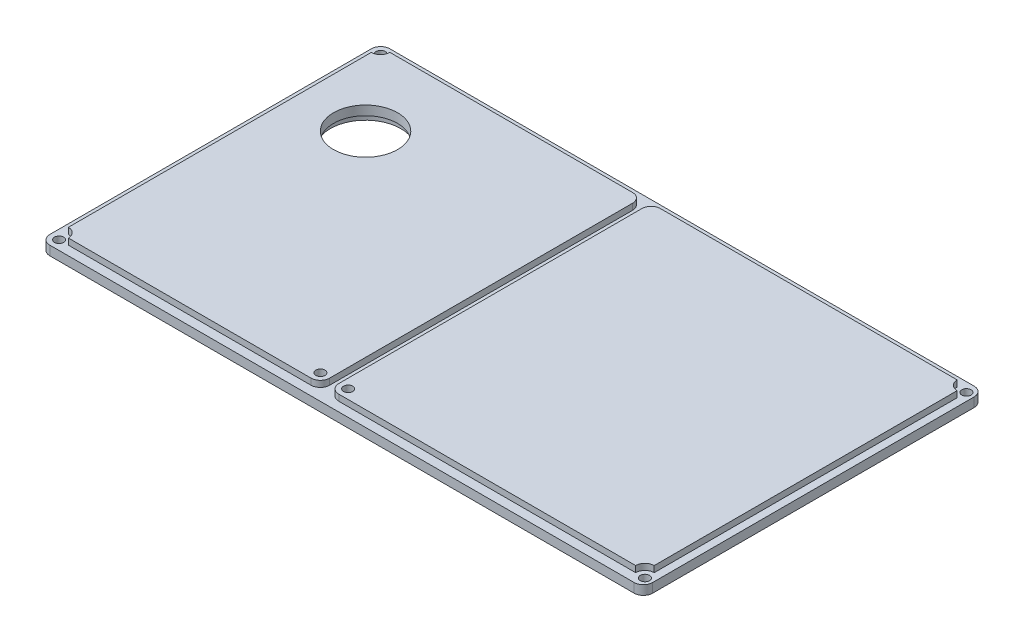
SolidWorks part; units mm, degrees
ref_plane "Front Plane" through (0, 0, 0) normal (0, 0, 1) x (1, 0, 0)
ref_plane "Top Plane" through (0, 0, 0) normal (0, 1, 0) x (1, 0, 0)
ref_plane "Right Plane" through (0, 0, 0) normal (1, 0, 0) x (0, 0, -1)
sketch "Sketch1" plane through (0, 0, 0) normal (0, 1, 0) x (1, 0, 0)
  line L1 (-97.5, 55) -> (97.5, 55)
  line L2 (-97.5, 55) -> (-97.5, -55)
  line L3 (-97.5, -55) -> (97.5, -55)
  line L4 (97.5, 55) -> (97.5, -55)
  line L5 (-97.5, 55) -> (97.5, -55) construction
  line L6 (-97.5, -55) -> (97.5, 55) construction
  point P0 (0, 0)
  dimension "D1" = 110
  dimension "D2" = 195
extrude "Boss-Extrude1" add sketch "Sketch1" along normal blind 3
sketch "Sketch2" plane through (0, 3, 0) normal (0, 1, 0) x (1, 0, 0)
  line L0 (-97.5, 0) -> (-94.5, 0) construction
  line L1 (-97.5, 55) -> (-97.5, -55) construction
  line L2 (-94.5, 0) -> (-94.5, 49)
  line L3 (-91.5, 52) -> (-13, 52)
  line L4 (-10, 49) -> (-10, -49)
  line L5 (-13, -52) -> (-91.5, -52)
  line L6 (-94.5, -49) -> (-94.5, 0)
  line L7 (-10, 0) -> (-7, 0) construction
  line L8 (-7, 0) -> (-7, 49)
  line L9 (-4, 52) -> (92, 52)
  line L10 (95, 49) -> (95, -49)
  line L11 (-7, 0) -> (-7, -49)
  line L12 (-4, -52) -> (92, -52)
  arc A0 (-7, -49) -> (-4, -52) centre (-4, -49) ccw
  arc A3 (-4, 52) -> (-7, 49) centre (-4, 49) ccw
  arc A4 (-13, 52) -> (-10, 49) centre (-13, 49) cw
  arc A5 (-13, -52) -> (-10, -49) centre (-13, -49) ccw
  arc A8 (-94.5, 49) -> (-91.5, 52) centre (-94.5, 52) ccw
  arc A9 (92, 52) -> (95, 49) centre (95, 52) ccw
  arc A10 (95, -49) -> (92, -52) centre (95, -52) ccw
  arc A11 (-91.5, -52) -> (-94.5, -49) centre (-94.5, -52) ccw
  point P17 (-7, -52)
  point P20 (95, -52)
  point P29 (-10, -52)
  point P32 (-94.5, -52)
  point P35 (-94.5, 52)
  dimension "D5" = 3
  dimension "D1" = 52
  dimension "D2" = 52
  dimension "D3" = 84.5
  dimension "D4" = 102
extrude "Boss-Extrude2" add sketch "Sketch2" along normal blind 2
sketch "Sketch4" plane through (0, 3, 0) normal (0, 1, 0) x (1, 0, 0)
  circle A0 centre (-94.5, 52) radius 1.5
  circle A1 centre (95, 52) radius 1.5
  circle A2 centre (95, -52) radius 1.5
  circle A3 centre (-94.5, -52) radius 1.5
extrude "Cut-Extrude2" cut sketch "Sketch4" against normal through all
fillet "Fillet1" radius 3 4 edges at (-97.5, 1.5, 55) (97.5, 1.5, 55) (97.5, 1.5, -55) (-97.5, 1.5, -55)
sketch "Sketch5" plane through (0, 5, 0) normal (0, 1, 0) x (1, 0, 0)
  circle A0 centre (-13, -49) radius 1.5
  circle A1 centre (-4, -49) radius 1.5
extrude "Cut-Extrude3" cut sketch "Sketch5" against normal through all
sketch "Sketch6" plane through (0, 5, 0) normal (0, 1, 0) x (1, 0, 0)
  line L0 (-94.5, 0) -> (-52.25, 0) construction
  line L1 (-94.5, 49) -> (-94.5, -49) construction
  line L2 (-52.25, 0) -> (-52.25, 52) construction
  line L3 (-13, 52) -> (-91.5, 52) construction
  line L4 (-52.25, 52) -> (-94.5, 0) construction
  circle A0 centre (-73.375, 26) radius 10.35
extrude "Cut-Extrude4" cut sketch "Sketch6" against normal through all
sketch "Sketch7" plane through (0, 0, 0) normal (0, -1, 0) x (1, 0, 0)
  circle A0 centre (-73.375, -26) radius 11.4
extrude "Cut-Extrude5" cut sketch "Sketch7" against normal blind 2
